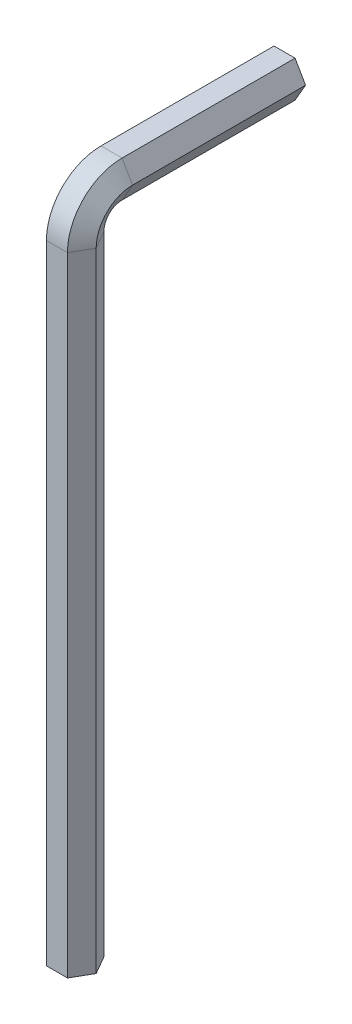
SolidWorks part; units mm, degrees
ref_plane "Front Plane" through (0, 0, 0) normal (0, 0, 1) x (1, 0, 0)
ref_plane "Top Plane" through (0, 0, 0) normal (0, 1, 0) x (1, 0, 0)
ref_plane "Right Plane" through (0, 0, 0) normal (1, 0, 0) x (0, 0, -1)
sketch "Sketch1" plane through (0, 0, 0) normal (1, 0, 0) x (0, 0, -1)
  line L0 (0, 0) -> (0, 69)
  line L1 (6, 75) -> (25, 75)
  line L2 (25, 73) -> (25, 30.8591) construction
  arc A0 (0, 69) -> (6, 75) centre (6, 69) cw
  dimension "D2" = 6
  dimension "D3" = 25
  dimension "D4" = 75
ref_plane "Plane8" through (0, 0, -25) normal (0, 0, 1) x (0, -1, 0)
sketch "Sketch4" plane through (0, 0, -25) normal (0, 0, 1) x (0, -1, 0)
  line L0 (-200073, 0) -> (199969.1409, 0) construction
  line L1 (-75, -1.1547) -> (-73, -2.3094)
  line L2 (-73, -2.3094) -> (-71, -1.1547)
  line L3 (-71, -1.1547) -> (-71, 1.1547)
  line L4 (-71, 1.1547) -> (-73, 2.3094)
  line L5 (-73, 2.3094) -> (-75, 1.1547)
  line L6 (-75, 1.1547) -> (-75, -1.1547)
  circle A0 centre (-73, 0) radius 2 construction
  point P1 (0, 0)
  point P11 (-75, 0)
  dimension "D1" = 4
sweep "Sweep4" add profiles "Sketch4" path "Sketch1"
